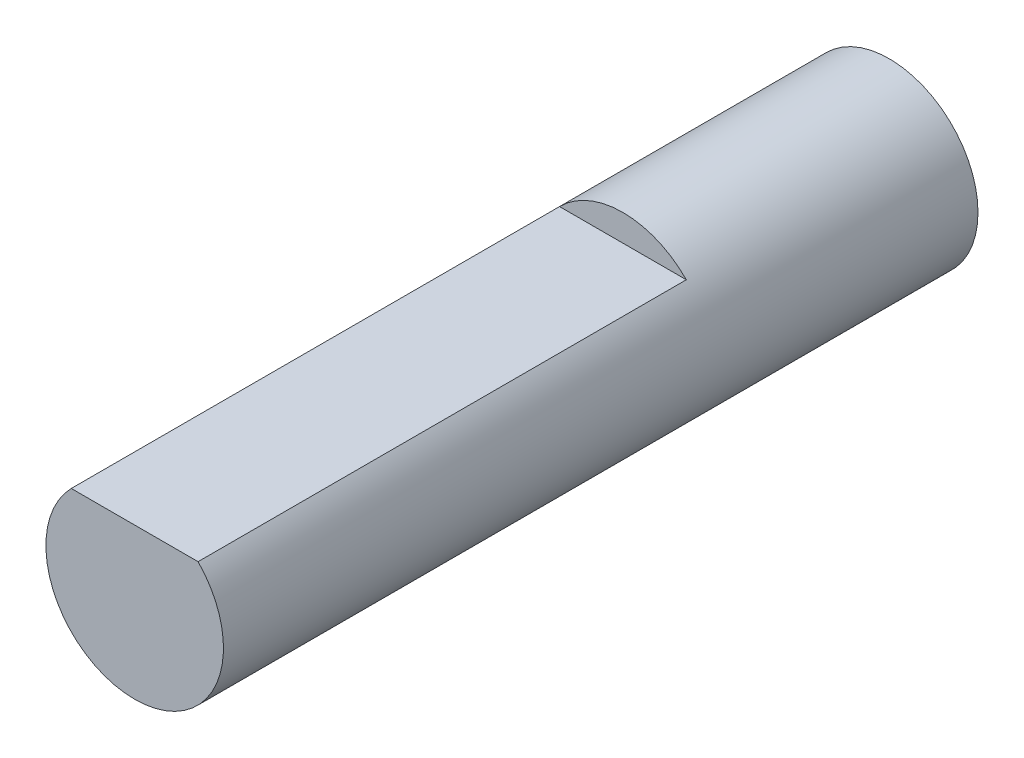
SolidWorks part; units mm, degrees
ref_plane "Alzado" through (0, 0, 0) normal (0, 0, 1) x (1, 0, 0)
ref_plane "Planta" through (0, 0, 0) normal (0, 1, 0) x (1, 0, 0)
ref_plane "Vista lateral" through (0, 0, 0) normal (1, 0, 0) x (0, 0, -1)
sketch "Croquis1" plane through (0, 0, 0) normal (0, 0, 1) x (1, 0, 0)
  circle A0 centre (0, 0) radius 2
  dimension "D1" = 4
extrude "Saliente-Extruir1" add sketch "Croquis1" along normal blind 17
sketch "Croquis2" plane through (0, 0, 17) normal (0, 0, 1) x (1, 0, 0)
  line L1 (-1.4283, 1.4) -> (1.4283, 1.4)
  circle A0 centre (0, 0) radius 2 construction
  arc A1 (1.4283, 1.4) -> (-1.4283, 1.4) centre (0, 0) ccw
  point P8 (0, 1.4)
extrude "Cortar-Extruir1" cut sketch "Croquis2" against normal blind 11
sketch "Croquis3" plane through (0, 0, 17) normal (0, 0, 1) x (1, 0, 0)
  line L0 (-1.4283, 1.4) -> (1.4283, 1.4)
  arc A0 (-1.4283, 1.4) -> (1.4283, 1.4) centre (0, 0) ccw
